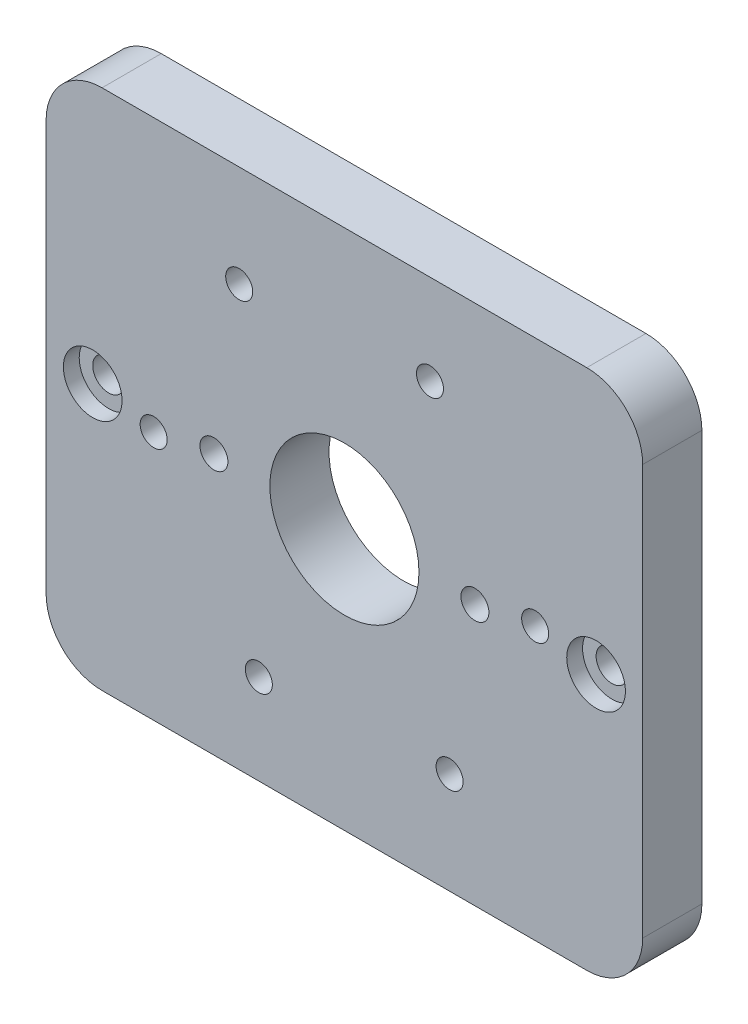
SolidWorks part; units mm, degrees
material "Aleación 6061"
ref_plane "Alzado" through (0, 0, 0) normal (0, 0, 1) x (1, 0, 0)
ref_plane "Planta" through (0, 0, 0) normal (0, 1, 0) x (1, 0, 0)
ref_plane "Vista lateral" through (0, 0, 0) normal (1, 0, 0) x (0, 0, -1)
sketch "Croquis1" plane through (0, 0, 0) normal (0, 0, 1) x (1, 0, 0)
  line L0 (126.4, -28) -> (178.4, -28)
  line L1 (184.4, -22) -> (184.4, 22)
  line L2 (178.4, 28) -> (126.4, 28)
  line L3 (120.4, 22) -> (120.4, -22)
  arc A0 (178.4, -28) -> (184.4, -22) centre (178.4, -22) ccw
  arc A1 (184.4, 22) -> (178.4, 28) centre (178.4, 22) ccw
  arc A2 (126.4, 28) -> (120.4, 22) centre (126.4, 22) ccw
  arc A3 (120.4, -22) -> (126.4, -28) centre (126.4, -22) ccw
  dimension "D1" = 6
  dimension "D2" = 6
  dimension "D3" = 6
  dimension "D4" = 6
  dimension "D5" = 126.4
  dimension "D6" = 28
  dimension "D7" = 178.4
  dimension "D8" = 28
  dimension "D9" = 184.4
  dimension "D10" = 22
  dimension "D11" = 184.4
  dimension "D12" = 22
  dimension "D13" = 178.4
  dimension "D14" = 28
  dimension "D15" = 126.4
  dimension "D16" = 28
  dimension "D17" = 120.4
  dimension "D18" = 22
  dimension "D19" = 120.4
  dimension "D20" = 22
extrude "Repisa_M6" add sketch "Croquis1" along normal blind 6.35 from offset 366.55
sketch "Croquis2" plane through (0, 0, 0) normal (0, 0, 1) x (1, 0, 0)
  circle A0 centre (172.8639, 1.2158) radius 1.45
  circle A1 centre (161.5791, 18.3302) radius 1.45
  circle A2 centre (141.1151, 17.1144) radius 1.45
  circle A3 centre (131.9361, -1.2158) radius 1.45
  circle A4 centre (143.2209, -18.3302) radius 1.45
  circle A5 centre (163.6849, -17.1144) radius 1.45
  circle A6 centre (152.4, 0) radius 8
  circle A7 centre (125.4, 0) radius 1.7
  circle A8 centre (179.4, 0) radius 1.7
  circle A9 centre (138.4, 0) radius 1.5
  circle A10 centre (166.4, 0) radius 1.5
  dimension "D1" = 2.9
  dimension "D2" = 2.9
  dimension "D3" = 2.9
  dimension "D4" = 2.9
  dimension "D5" = 2.9
  dimension "D6" = 2.9
  dimension "D7" = 16
  dimension "D8" = 3.4
  dimension "D9" = 3.4
  dimension "D10" = 3
  dimension "D11" = 3
  dimension "D12" = 172.8639
  dimension "D13" = 1.2158
  dimension "D14" = 161.5791
  dimension "D15" = 18.3302
  dimension "D16" = 141.1151
  dimension "D17" = 17.1144
  dimension "D18" = 131.9361
  dimension "D19" = 1.2158
  dimension "D20" = 143.2209
  dimension "D21" = 18.3302
  dimension "D22" = 163.6849
  dimension "D23" = 17.1144
  dimension "D24" = 152.4
  dimension "D25" = 125.4
  dimension "D26" = 179.4
  dimension "D27" = 138.4
  dimension "D28" = 166.4
extrude "Barrenos_M6_tornillos_pasadores" cut sketch "Croquis2" along normal blind 6.35 from offset 366.55
sketch "Croquis3" plane through (0, 0, 0) normal (0, 0, 1) x (1, 0, 0)
  circle A0 centre (172.8639, 1.2158) radius 2.5
  circle A1 centre (161.5791, 18.3302) radius 2.5
  circle A2 centre (141.1151, 17.1144) radius 2.5
  circle A3 centre (131.9361, -1.2158) radius 2.5
  circle A4 centre (143.2209, -18.3302) radius 2.5
  circle A5 centre (163.6849, -17.1144) radius 2.5
  dimension "D1" = 5
  dimension "D2" = 5
  dimension "D3" = 5
  dimension "D4" = 5
  dimension "D5" = 5
  dimension "D6" = 5
  dimension "D7" = 172.8639
  dimension "D8" = 1.2158
  dimension "D9" = 161.5791
  dimension "D10" = 18.3302
  dimension "D11" = 141.1151
  dimension "D12" = 17.1144
  dimension "D13" = 131.9361
  dimension "D14" = 1.2158
  dimension "D15" = 143.2209
  dimension "D16" = 18.3302
  dimension "D17" = 163.6849
  dimension "D18" = 17.1144
extrude "Refrentado_M2-5" cut sketch "Croquis3" along normal blind 2.6 from offset 366.55
sketch "Croquis4" plane through (0, 0, 0) normal (0, 0, 1) x (1, 0, 0)
  circle A0 centre (125.4, 0) radius 3.15
  circle A1 centre (179.4, 0) radius 3.15
  dimension "D1" = 6.3
  dimension "D2" = 6.3
  dimension "D3" = 125.4
  dimension "D4" = 179.4
extrude "Avellanado_M3" cut sketch "Croquis4" along normal blind 1.7 from offset 371.2
